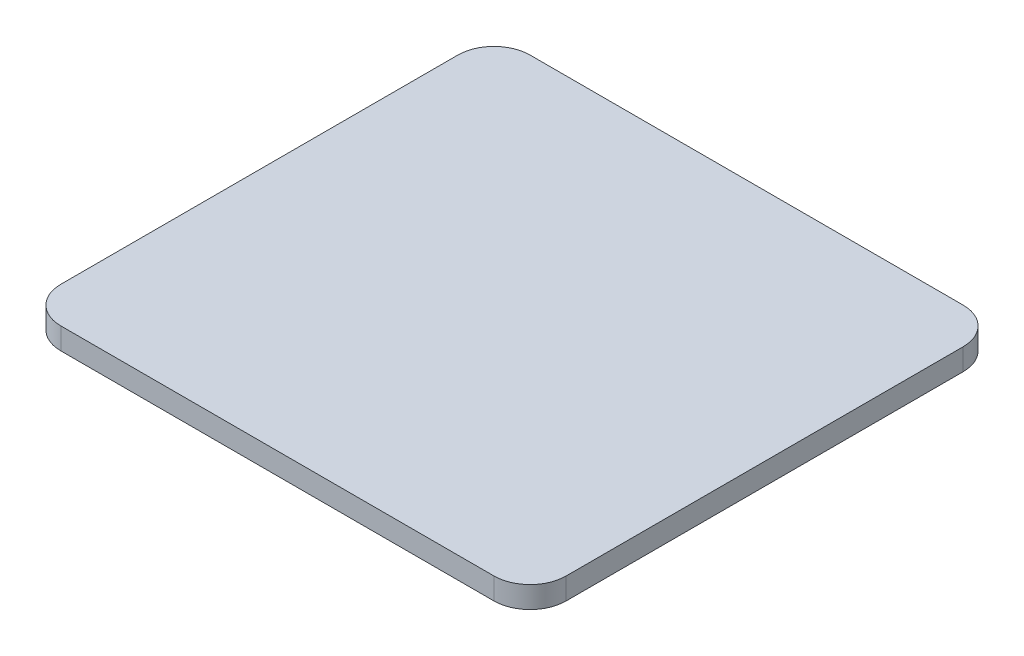
SolidWorks part; units mm, degrees
ref_plane "Front Plane" through (0, 0, 0) normal (0, 0, 1) x (1, 0, 0)
ref_plane "Top Plane" through (0, 0, 0) normal (0, 1, 0) x (1, 0, 0)
ref_plane "Right Plane" through (0, 0, 0) normal (1, 0, 0) x (0, 0, -1)
sketch "Sketch1" plane through (0, 0, 0) normal (0, 1, 0) x (1, 0, 0)
  line L1 (-35, 32.5) -> (35, 32.5)
  line L2 (-35, 32.5) -> (-35, -32.5)
  line L3 (-35, -32.5) -> (35, -32.5)
  line L4 (35, 32.5) -> (35, -32.5)
  line L5 (-35, 32.5) -> (35, -32.5) construction
  line L6 (-35, -32.5) -> (35, 32.5) construction
  point P0 (0, 0)
  dimension "D1" = 70
  dimension "D2" = 65
extrude "Boss-Extrude1" add sketch "Sketch1" along normal blind 3
fillet "Fillet1" radius 5 4 edges at (-35, 1.5, -32.5) (35, 1.5, -32.5) (35, 1.5, 32.5) (-35, 1.5, 32.5)
